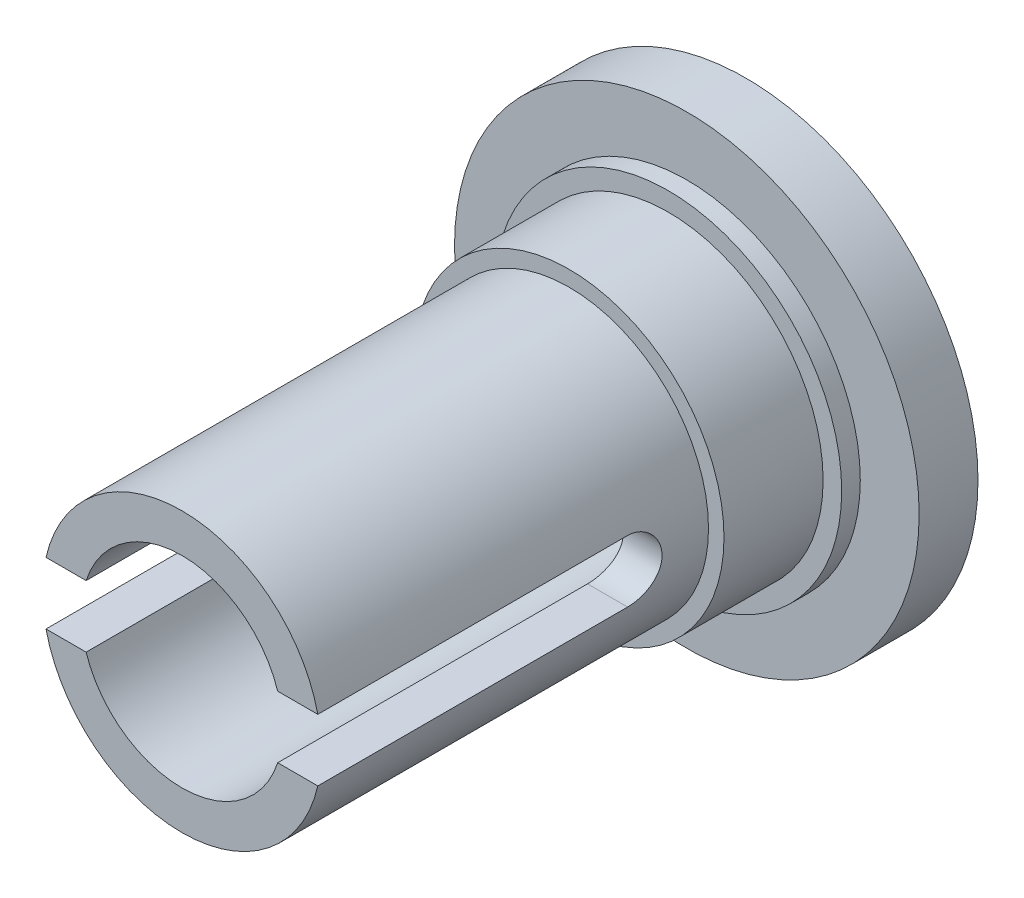
SolidWorks part; units mm, degrees
ref_plane "Front Plane" through (0, 0, 0) normal (0, 0, 1) x (1, 0, 0)
ref_plane "Top Plane" through (0, 0, 0) normal (0, 1, 0) x (1, 0, 0)
ref_plane "Right Plane" through (0, 0, 0) normal (1, 0, 0) x (0, 0, -1)
sketch "Sketch1" plane through (0, 0, 0) normal (0, 0, 1) x (1, 0, 0)
  circle A0 centre (0, 0) radius 9.525
  dimension "D1" = 19.05
extrude "Boss-Extrude1" add sketch "Sketch1" along normal blind 3.175
sketch "Sketch2" plane through (0, 0, 3.175) normal (0, 0, 1) x (1, 0, 0)
  circle A0 centre (0, 0) radius 6.35
  dimension "D1" = 12.7
extrude "Boss-Extrude2" add sketch "Sketch2" along normal blind 4.064
sketch "Sketch3" plane through (0, 0, 7.239) normal (0, 0, 1) x (1, 0, 0)
  circle A0 centre (0, 0) radius 5.715
  dimension "D1" = 11.43
extrude "Boss-Extrude3" add sketch "Sketch3" along normal blind 15.875
sketch "Sketch4" plane through (0, 0, 23.114) normal (0, 0, 1) x (1, 0, 0)
  circle A0 centre (0, 0) radius 4.1275
  circle A1 centre (0, 0) radius 5.715 construction
  dimension "D1" = 1.5875
extrude "Cut-Extrude1" cut sketch "Sketch4" against normal through all
sketch "Sketch5" plane through (0, 0, 0) normal (1, 0, 0) x (0, 0, -1)
  line L0 (-7.239, 6.35) -> (-7.239, -6.35) construction
  line L1 (-23.114, 1.27) -> (-10.414, 1.27)
  line L2 (-23.114, 1.27) -> (-23.114, -1.27)
  line L3 (-23.114, -1.27) -> (-10.414, -1.27)
  line L4 (-10.414, 1.27) -> (-10.414, -1.27)
  line L5 (-23.114, 5.715) -> (-23.114, -5.715) construction
  arc A0 (-10.414, 1.27) -> (-10.414, -1.27) centre (-10.414, 0) cw
  dimension "D1" = 3.175
  dimension "D2" = 2.54
extrude "Cut-Extrude2" cut sketch "Sketch5" against normal mid plane 19.05 contours L4 L1 L2 L3 | A0 L4
sketch "Sketch7" plane through (0, 0, 3.175) normal (0, 0, 1) x (1, 0, 0)
  circle A0 centre (0, 0) radius 7.112
  circle A1 centre (0, 0) radius 9.525
  circle A2 centre (0, 0) radius 9.525 construction
  dimension "D1" = 14.224
extrude "Cut-Extrude4" cut sketch "Sketch7" against normal blind 0.762
